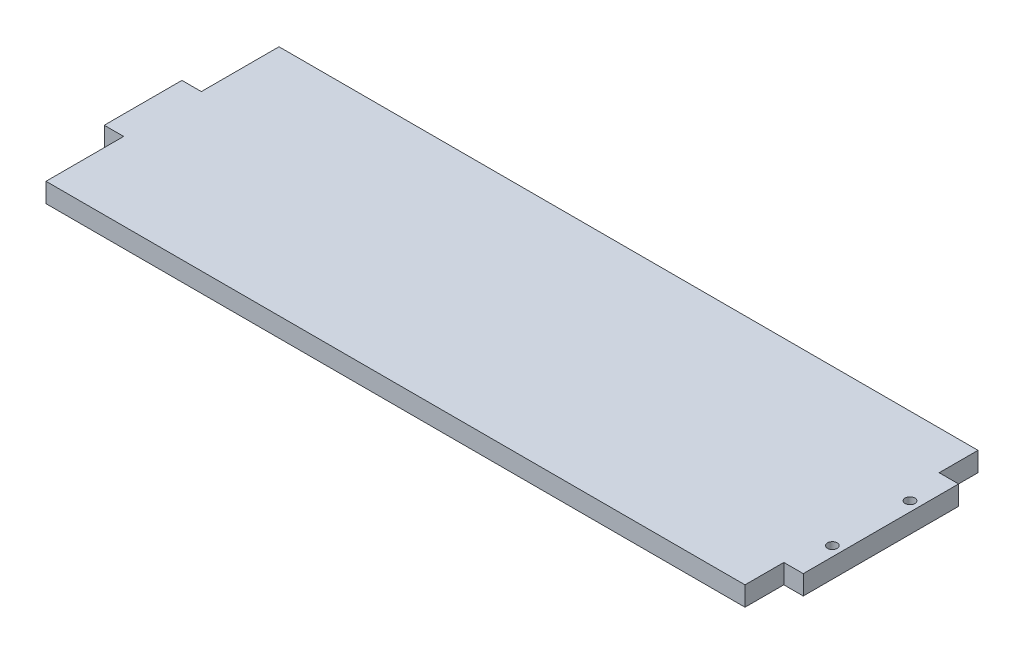
SolidWorks part; units mm, degrees
material "6061 Alloy"
ref_plane "Front Plane" through (0, 0, 0) normal (0, 0, 1) x (1, 0, 0)
ref_plane "Top Plane" through (0, 0, 0) normal (0, 1, 0) x (1, 0, 0)
ref_plane "Right Plane" through (0, 0, 0) normal (1, 0, 0) x (0, 0, -1)
sketch "Sketch1" plane through (0, 0, 0) normal (0, 1, 0) x (1, 0, 0)
  line L0 (-75.2148, -28.3223) -> (153.3852, -28.3223)
  line L1 (153.3852, -104.5223) -> (-75.2148, -104.5223)
  line L2 (159.7352, -66.4223) -> (159.7352, -41.0223)
  line L3 (159.7352, -41.0223) -> (153.3852, -41.0223)
  line L4 (159.7352, -66.4223) -> (159.7352, -91.8223)
  line L5 (159.7352, -91.8223) -> (153.3852, -91.8223)
  line L6 (153.3852, -28.3223) -> (153.3852, -41.0223)
  line L7 (153.3852, -91.8223) -> (153.3852, -104.5223)
  line L8 (-75.2148, -28.3223) -> (-75.2148, -53.7223)
  line L9 (-75.2148, -53.7223) -> (-81.5648, -53.7223)
  line L10 (-75.2148, -104.5223) -> (-75.2148, -79.1223)
  line L11 (-75.2148, -79.1223) -> (-81.5648, -79.1223)
  line L12 (-81.5648, -53.7223) -> (-81.5648, -79.1223)
  circle A0 centre (156.5602, -53.7223) radius 1.5875
  circle A1 centre (156.5602, -79.1223) radius 1.5875
extrude "Boss-Extrude1" add sketch "Sketch1" along normal blind 6.35
